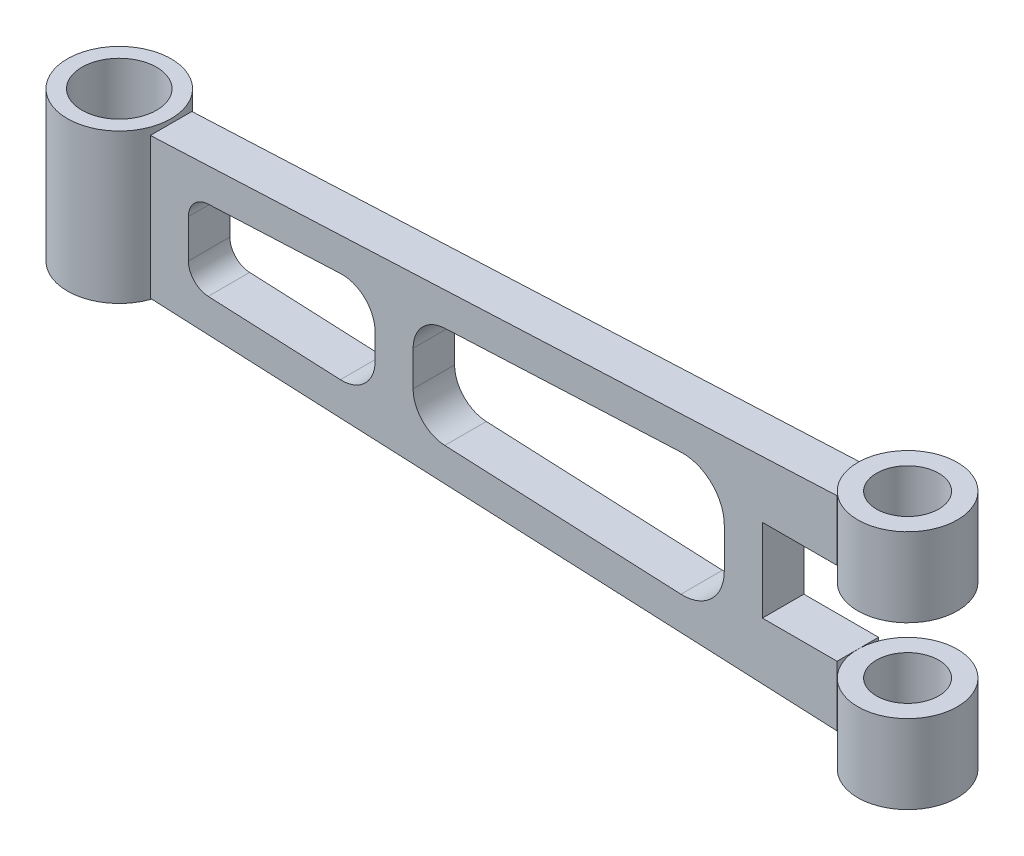
SolidWorks part; units mm, degrees
ref_plane "Front Plane" through (0, 0, 0) normal (0, 0, 1) x (1, 0, 0)
ref_plane "Top Plane" through (0, 0, 0) normal (0, 1, 0) x (1, 0, 0)
ref_plane "Right Plane" through (0, 0, 0) normal (1, 0, 0) x (0, 0, -1)
sketch "Sketch1" plane through (0, 0, 0) normal (0, 0, 1) x (1, 0, 0)
  line L9 (0, 17) -> (0, -17)
  line L10 (0, 0) -> (295, 0) construction
  line L12 (0, 17) -> (165.5, 24.5528)
  line L13 (165.5, 24.5528) -> (165.5, 10)
  line L14 (165.5, 10) -> (147.5, 10)
  line L15 (147.5, 10) -> (147.5, -10)
  line L16 (147.5, -10) -> (165.5, -10)
  line L17 (165.5, -10) -> (165.5, -24.5528)
  line L18 (165.5, -24.5528) -> (0, -17)
  line L19 (9.16, 0) -> (9.16, 4.6327)
  line L20 (13.9321, 9.6275) -> (45.7953, 11.0816)
  line L21 (54.16, 3.0899) -> (54.16, -3.0899)
  line L22 (45.7953, -11.0816) -> (13.9321, -9.6275)
  line L23 (9.16, -4.6327) -> (9.16, 0)
  line L24 (63.32, 4.2381) -> (63.32, -4.2381)
  line L25 (70.9553, -12.2298) -> (127.8641, -14.8269)
  line L26 (138.32, -4.8373) -> (138.32, 4.8373)
  line L27 (127.8641, 14.8269) -> (70.9553, 12.2298)
  line L28 (0, 0) -> (-36.6365, 0) construction
  line L29 (-12.5, 27.0815) -> (-12.5, -23.4593) construction
  line L30 (27.5, 18.255) -> (27.5, -18.255) construction
  line L31 (165.5, 10) -> (203.9389, 10)
  line L32 (177.5, 31.2835) -> (177.5, -21.2292) construction
  line L33 (189.5, 32.339) -> (189.5, -21.2292)
  arc A0 (54.16, -3.0899) -> (45.7953, -11.0816) centre (46.16, -3.0899) cw
  arc A1 (54.16, 3.0899) -> (45.7953, 11.0816) centre (46.16, 3.0899) ccw
  arc A2 (13.9321, -9.6275) -> (9.16, -4.6327) centre (14.16, -4.6327) cw
  arc A3 (9.16, 4.6327) -> (13.9321, 9.6275) centre (14.16, 4.6327) cw
  arc A4 (70.9553, -12.2298) -> (63.32, -4.2381) centre (71.32, -4.2381) cw
  arc A5 (63.32, 4.2381) -> (70.9553, 12.2298) centre (71.32, 4.2381) cw
  arc A6 (138.32, -4.8373) -> (127.8641, -14.8269) centre (128.32, -4.8373) cw
  arc A7 (138.32, 4.8373) -> (127.8641, 14.8269) centre (128.32, 4.8373) ccw
  point P0 (0, 0)
  point P5 (147.5, 0)
  dimension "D12" = 8
  dimension "D13" = 5
  dimension "D14" = 8
  dimension "D15" = 10
  dimension "D1" = 20
  dimension "D2" = 165.5
  dimension "D3" = 165.5
  dimension "D4" = 34
  dimension "D5" = 45
  dimension "D6" = 8
  dimension "D7" = 8
  dimension "D8" = 75
  dimension "D9" = 12.5
  dimension "D10" = 36.51
  dimension "D11" = 40
  dimension "D16" = 12
  dimension "D17" = 12
  dimension "D18" = 42
  dimension "D19" = 9.16
  dimension "D20" = 9.16
  dimension "D21" = 8
  dimension "D22" = 8
extrude "Boss-Extrude1" add sketch "Sketch1" against normal blind 10 contours L18 L17 L16 L15 L14 L13 L12 L9 A7 L26 A6 L25 A4 L24 A5 L27 L19 A3 L20 A1 L21 A0 L22 A2 L23
sketch "Sketch2" plane through (0, 0, 0) normal (0, 1, 0) x (1, 0, 0)
  line L0 (0, 5) -> (-12.5, 5) construction
  line L1 (0, 10) -> (0, 0) construction
  line L2 (-12.5, -3.4063) -> (-12.5, 5) construction
  circle A0 centre (-12.5, 5) radius 12.5
  circle A1 centre (-12.5, 5) radius 9
  dimension "D2" = 18
  dimension "D1" = 12.5
extrude "Boss-Extrude2" add sketch "Sketch2" along normal mid plane 36 separate body
ref_plane "Plane1" through (0, -10, 0) normal (0, 1, 0) x (1, 0, 0)
sketch "Sketch3" plane through (0, -10, 0) normal (0, 1, 0) x (1, 0, 0)
  line L0 (165.5, 5) -> (177.5, 5) construction
  line L1 (165.5, 10) -> (165.5, 0) construction
  line L2 (177.5, -7.9344) -> (177.5, 5) construction
  circle A0 centre (177.5, 5) radius 12
  circle A1 centre (177.5, 5) radius 7.5
  dimension "D2" = 15
  dimension "D1" = 12
extrude "Boss-Extrude3" add sketch "Sketch3" against normal blind 19 separate body
mirror "Mirror2" about plane through (0, 0, 0) normal (0, 1, 0) of bodies 103
